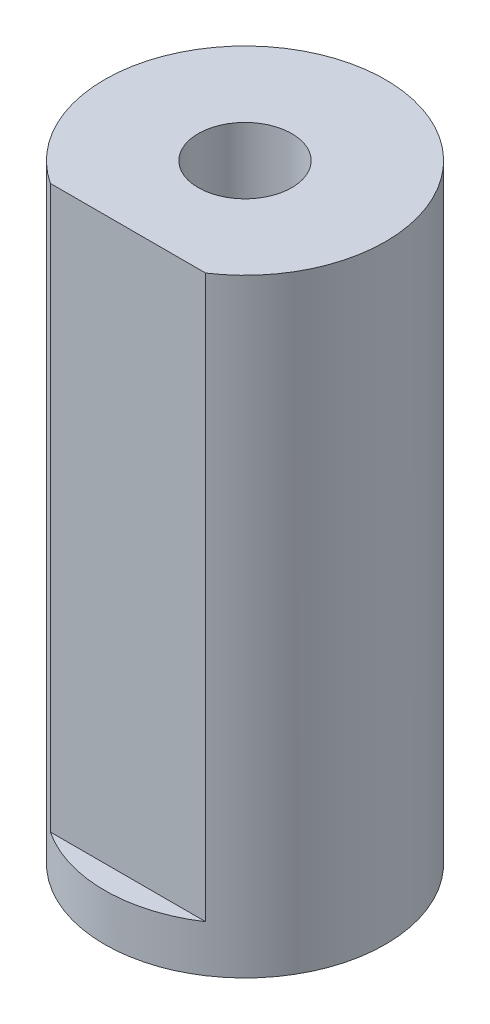
SolidWorks part; units mm, degrees
ref_plane "Front Plane" through (0, 0, 0) normal (0, 0, 1) x (1, 0, 0)
ref_plane "Top Plane" through (0, 0, 0) normal (0, 1, 0) x (1, 0, 0)
ref_plane "Right Plane" through (0, 0, 0) normal (1, 0, 0) x (0, 0, -1)
sketch "Sketch1" plane through (0, 0, 0) normal (0, 1, 0) x (1, 0, 0)
  circle A0 centre (0, 0) radius 3
  dimension "D1" = 6
extrude "Boss-Extrude1" add sketch "Sketch1" along normal blind 13
sketch "Sketch2" plane through (0, 13, 0) normal (0, 1, 0) x (1, 0, 0)
  circle A0 centre (0, 0) radius 1
  dimension "D1" = 2
extrude "Cut-Extrude1" cut sketch "Sketch2" against normal blind 13
sketch "Sketch3" plane through (0, 13, 0) normal (0, 1, 0) x (1, 0, 0)
  line L1 (1.6583, -2.5) -> (-1.6583, -2.5)
  circle A0 centre (0, 0) radius 3 construction
  circle A2 centre (0, 0) radius 3
  circle A3 centre (0, 0) radius 3
  circle M5 centre (0, 0) radius 3
  dimension "D1" = 0
  dimension "D2" = 2.5
extrude "Cut-Extrude2" cut sketch "Sketch3" against normal blind 12 contours L1 M5
